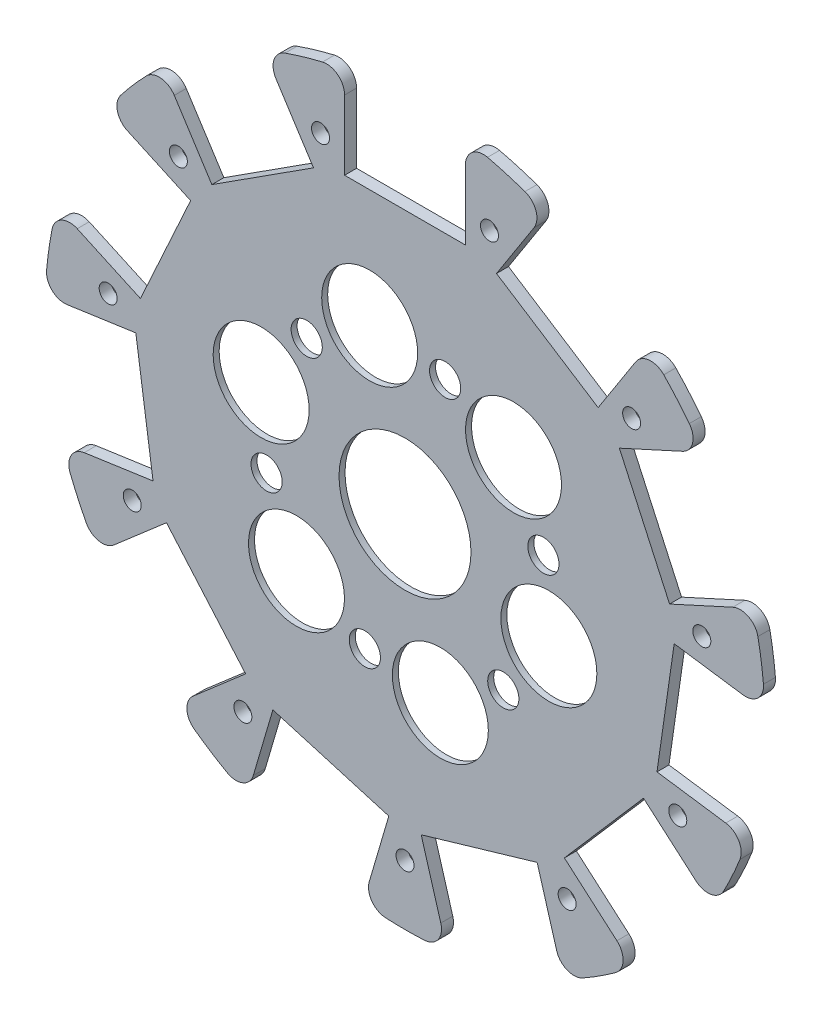
SolidWorks part; units mm, degrees
ref_plane "Front Plane" through (0, 0, 0) normal (0, 0, 1) x (1, 0, 0)
ref_plane "Top Plane" through (0, 0, 0) normal (0, 1, 0) x (1, 0, 0)
ref_plane "Right Plane" through (0, 0, 0) normal (1, 0, 0) x (0, 0, -1)
sketch "Sketch1" plane through (0, 0, 0) normal (0, 0, 1) x (1, 0, 0)
  line L44 (21.5207, 52.1193) -> (15.2567, 42.3722)
  line L47 (-10.0734, 55.4805) -> (-10.0734, 43.8941)
  line L48 (-10.0734, 43.8941) -> (10.0734, 43.8941)
  line L49 (10.0734, 55.4805) -> (10.0734, 43.8941)
  line L51 (38.4693, 41.2271) -> (32.2052, 31.48)
  line L52 (15.2567, 42.3722) -> (32.2052, 31.48)
  line L53 (46.2822, 32.2105) -> (35.7428, 27.3974)
  line L55 (54.6515, 13.8844) -> (44.1121, 9.0712)
  line L56 (35.7428, 27.3974) -> (44.1121, 9.0712)
  line L57 (56.3494, 2.0752) -> (44.8809, 3.7241)
  line L59 (53.4822, -17.8666) -> (42.0137, -16.2176)
  line L60 (44.8809, 3.7241) -> (42.0137, -16.2176)
  line L61 (48.526, -28.719) -> (39.7696, -21.1316)
  line L63 (35.3327, -43.945) -> (26.5763, -36.3575)
  line L64 (39.7696, -21.1316) -> (26.5763, -36.3575)
  line L65 (25.296, -50.3952) -> (22.0318, -39.2781)
  line L67 (5.9653, -56.0712) -> (2.701, -44.9541)
  line L68 (22.0318, -39.2781) -> (2.701, -44.9541)
  line L69 (-5.9653, -56.0712) -> (-2.701, -44.9541)
  line L71 (-25.296, -50.3952) -> (-22.0318, -39.2781)
  line L72 (-2.701, -44.9541) -> (-22.0318, -39.2781)
  line L73 (-35.3327, -43.945) -> (-26.5763, -36.3575)
  line L75 (-48.526, -28.719) -> (-39.7696, -21.1316)
  line L76 (-26.5763, -36.3575) -> (-39.7696, -21.1316)
  line L77 (-53.4822, -17.8666) -> (-42.0137, -16.2176)
  line L79 (-56.3494, 2.0752) -> (-44.8809, 3.7241)
  line L80 (-42.0137, -16.2176) -> (-44.8809, 3.7241)
  line L81 (-54.6515, 13.8844) -> (-44.1121, 9.0712)
  line L83 (-46.2822, 32.2105) -> (-35.7428, 27.3974)
  line L84 (-44.1121, 9.0712) -> (-35.7428, 27.3974)
  line L85 (-38.4693, 41.2271) -> (-32.2052, 31.48)
  line L87 (-21.5207, 52.1193) -> (-15.2567, 42.3722)
  line L88 (-32.2052, 31.48) -> (-15.2567, 42.3722)
  arc A33 (-43.1506, 41.6896) -> (-47.4063, 36.7783) centre (0, 0) ccw
  arc A34 (-13.7615, 58.4005) -> (-19.9968, 56.5697) centre (0, 0) ccw
  arc A35 (19.9968, 56.5697) -> (13.7615, 58.4005) centre (0, 0) ccw
  arc A36 (47.4063, 36.7783) -> (43.1506, 41.6896) centre (0, 0) ccw
  arc A37 (59.7646, 5.3101) -> (58.8397, 11.7426) centre (0, 0) ccw
  arc A38 (53.148, -27.844) -> (55.8476, -21.9327) centre (0, 0) ccw
  arc A39 (29.6574, -52.1578) -> (35.1243, -48.6444) centre (0, 0) ccw
  arc A40 (-3.2493, -59.912) -> (3.2493, -59.912) centre (0, 0) ccw
  arc A41 (-35.1243, -48.6444) -> (-29.6574, -52.1578) centre (0, 0) ccw
  arc A42 (-55.8476, -21.9327) -> (-53.148, -27.844) centre (0, 0) ccw
  arc A43 (-58.8397, 11.7426) -> (-59.7646, 5.3101) centre (0, 0) ccw
  arc A44 (-54.6515, 13.8844) -> (-58.8397, 11.7426) centre (-55.8977, 11.1555) ccw
  arc A45 (-56.3494, 2.0752) -> (-59.7646, 5.3101) centre (-56.7763, 5.0446) cw
  arc A46 (-48.526, -28.719) -> (-53.148, -27.844) centre (-50.4906, -26.4518) cw
  arc A47 (-53.4822, -17.8666) -> (-55.8476, -21.9327) centre (-53.0553, -20.836) ccw
  arc A48 (-25.296, -50.3952) -> (-29.6574, -52.1578) centre (-28.1745, -49.55) cw
  arc A49 (-35.3327, -43.945) -> (-35.1243, -48.6444) centre (-33.3681, -46.2122) ccw
  arc A50 (-5.9653, -56.0712) -> (-3.2493, -59.912) centre (-3.0868, -56.9164) ccw
  arc A51 (5.9653, -56.0712) -> (3.2493, -59.912) centre (3.0868, -56.9164) cw
  arc A52 (35.3327, -43.945) -> (35.1243, -48.6444) centre (33.3681, -46.2122) cw
  arc A53 (25.296, -50.3952) -> (29.6574, -52.1578) centre (28.1745, -49.55) ccw
  arc A54 (48.526, -28.719) -> (53.148, -27.844) centre (50.4906, -26.4518) ccw
  arc A55 (53.4822, -17.8666) -> (55.8476, -21.9327) centre (53.0553, -20.836) cw
  arc A56 (56.3494, 2.0752) -> (59.7646, 5.3101) centre (56.7763, 5.0446) ccw
  arc A57 (54.6515, 13.8844) -> (58.8397, 11.7426) centre (55.8977, 11.1555) cw
  arc A58 (46.2822, 32.2105) -> (47.4063, 36.7783) centre (45.036, 34.9394) ccw
  arc A59 (38.4693, 41.2271) -> (43.1506, 41.6896) centre (40.9931, 39.6052) cw
  arc A60 (21.5207, 52.1193) -> (19.9968, 56.5697) centre (18.997, 53.7412) ccw
  arc A61 (10.0734, 55.4805) -> (13.7615, 58.4005) centre (13.0734, 55.4805) cw
  arc A62 (-10.0734, 55.4805) -> (-13.7615, 58.4005) centre (-13.0734, 55.4805) ccw
  arc A63 (-21.5207, 52.1193) -> (-19.9968, 56.5697) centre (-18.997, 53.7412) cw
  arc A64 (-38.4693, 41.2271) -> (-43.1506, 41.6896) centre (-40.9931, 39.6052) ccw
  arc A65 (-46.2822, 32.2105) -> (-47.4063, 36.7783) centre (-45.036, 34.9394) cw
  point P3 (-57.9879, 15.408)
  point P51 (0, 0)
  point P55 (-57.1127, -18.3885)
  point P60 (-38.1047, -46.3469)
  point P63 (-6.9987, -59.5904)
  point P70 (26.3294, -53.9144)
  point P73 (51.298, -31.121)
  point P78 (59.9799, 1.5532)
  point P83 (49.6186, 33.7342)
  point P88 (23.5037, 55.2048)
  point P93 (-10.0734, 59.1483)
  dimension "D1" = 120
  dimension "D2" = 3
extrude "Boss-Extrude1" add sketch "Sketch1" along normal blind 2
sketch "Sketch4" plane through (0, 0, 2) normal (0, 0, 1) x (1, 0, 0)
  line L0 (0, 17.7708) -> (0, 0) construction
  line L1 (0, 0) -> (-14.0866, 47.9746) construction
  circle A0 centre (-14.0866, 47.9746) radius 1.5
  circle A1 centre (14.0866, 47.9746) radius 1.5
  circle A2 centre (37.7875, 32.743) radius 1.5
  circle A3 centre (49.4911, 7.1157) radius 1.5
  circle A4 centre (45.4816, -20.7708) radius 1.5
  circle A5 centre (27.032, -42.0627) radius 1.5
  circle A6 centre (0, -50) radius 1.5
  circle A7 centre (-27.032, -42.0627) radius 1.5
  circle A8 centre (-45.4816, -20.7708) radius 1.5
  circle A9 centre (-49.4911, 7.1157) radius 1.5
  circle A10 centre (-37.7875, 32.743) radius 1.5
  point P28 (0, 0)
  dimension "D1" = 3
  dimension "D2" = 50
  dimension "D3" = 16.364
extrude "Cut-Extrude3" cut sketch "Sketch4" against normal blind 2
sketch "Sketch6" plane through (0, 0, 0) normal (0, 0, -1) x (-1, 0, 0)
  circle A0 centre (0, 0) radius 35
  dimension "D1" = 70
extrude "Cut-Extrude4" cut sketch "Sketch6" against normal blind 1
sketch "Sketch7" plane through (0, 0, 1) normal (0, 0, -1) x (-1, 0, 0)
  line L0 (-18.0934, 17.252) -> (0, 0) construction
  line L1 (0, 0) -> (-6.6911, 22.788) construction
  line L2 (0, 0) -> (0, 8.8147) construction
  circle A0 centre (0, 0) radius 11
  circle A1 centre (-6.6911, 22.788) radius 2.6
  circle A2 centre (-18.0934, 17.252) radius 8
  circle A3 centre (5.894, 24.2953) radius 8
  circle A4 centre (16.3894, 17.1887) radius 2.6
  circle A5 centre (23.9873, 7.0433) radius 8
  circle A6 centre (23.0805, -5.5993) radius 2.6
  circle A7 centre (18.0934, -17.252) radius 8
  circle A8 centre (6.6911, -22.788) radius 2.6
  circle A9 centre (-5.894, -24.2953) radius 8
  circle A10 centre (-16.3894, -17.1887) radius 2.6
  circle A11 centre (-23.9873, -7.0433) radius 8
  circle A12 centre (-23.0805, 5.5993) radius 2.6
  point P30 (0, 0)
  dimension "D1" = 22
  dimension "D2" = 16
  dimension "D3" = 5.2
  dimension "D4" = 23.75
  dimension "D5" = 25
  dimension "D6" = 16.364
  dimension "D7" = 30
  dimension "D8" = 6
extrude "Cut-Extrude5" cut sketch "Sketch7" against normal blind 10
